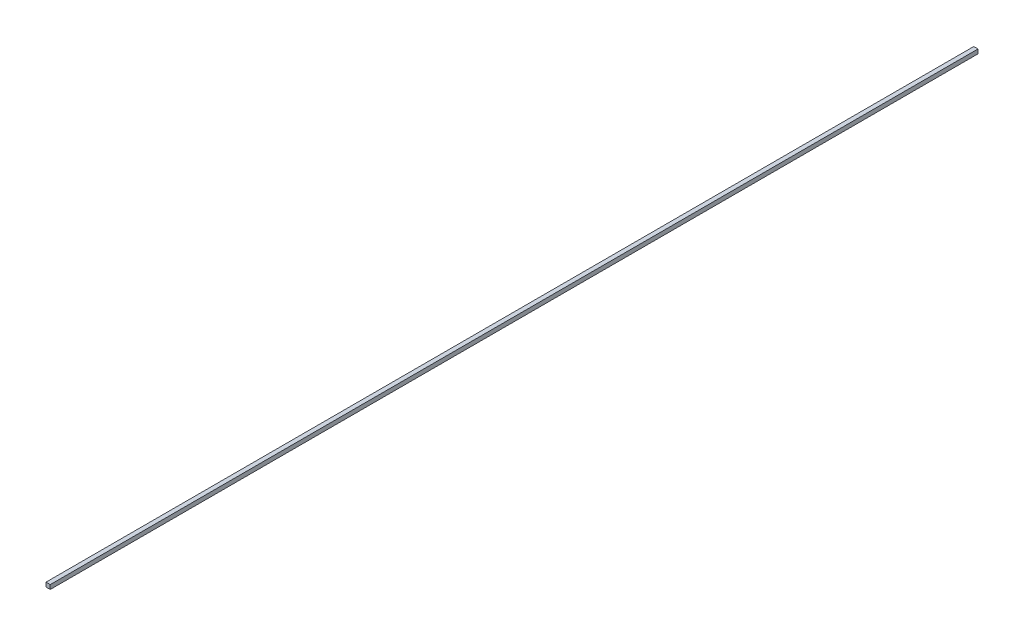
SolidWorks part; units mm, degrees
ref_plane "前视基准面" through (0, 0, 0) normal (0, 0, 1) x (1, 0, 0)
ref_plane "上视基准面" through (0, 0, 0) normal (0, 1, 0) x (1, 0, 0)
ref_plane "右视基准面" through (0, 0, 0) normal (1, 0, 0) x (0, 0, -1)
sketch "草图1" plane through (0, 0, 0) normal (0, 0, 1) x (1, 0, 0)
  line L1 (0, 0) -> (3, 0)
  line L2 (0, 0) -> (0, 3)
  line L3 (0, 3) -> (3, 3)
  line L4 (3, 0) -> (3, 3)
  dimension "D1" = 3
extrude "凸台-拉伸1" add sketch "草图1" along normal blind 655
